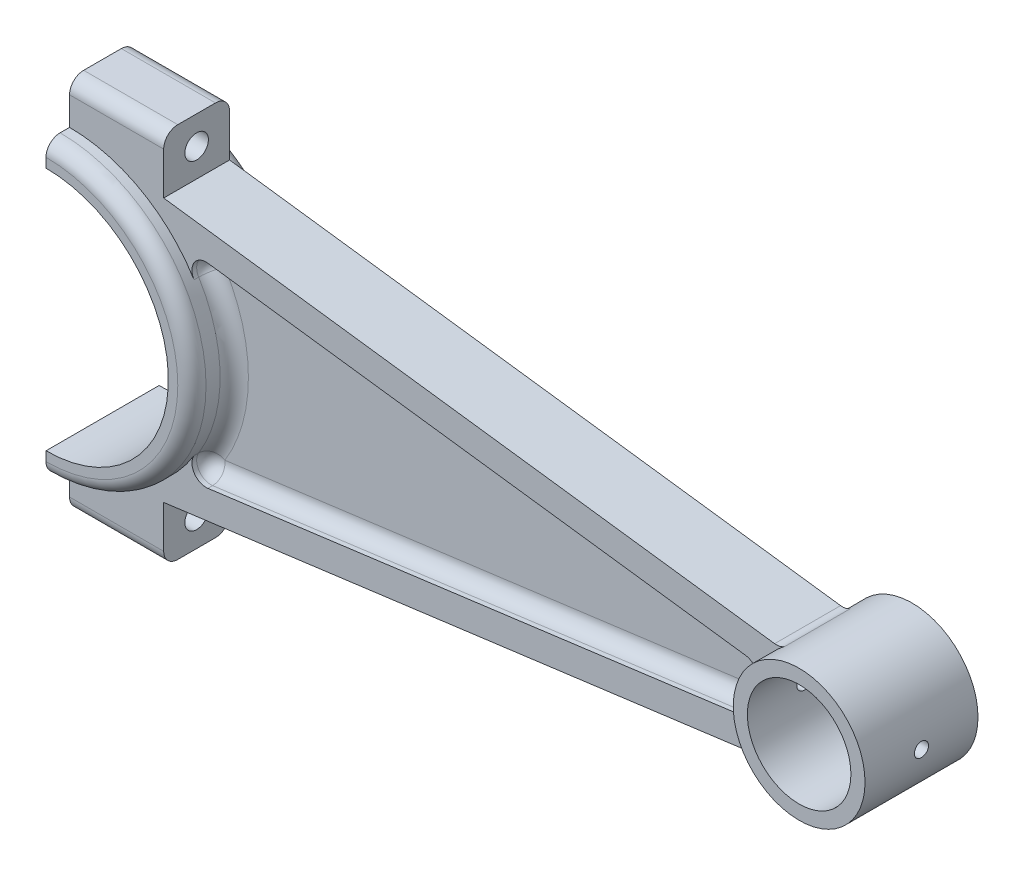
SolidWorks part; units mm, degrees
ref_plane "前视基准面" through (0, 0, 0) normal (0, 0, 1) x (1, 0, 0)
ref_plane "上视基准面" through (0, 0, 0) normal (0, 1, 0) x (1, 0, 0)
ref_plane "右视基准面" through (0, 0, 0) normal (1, 0, 0) x (0, 0, -1)
sketch "草图1" plane through (0, 0, 0) normal (0, 0, 1) x (1, 0, 0)
  line L0 (0, -40) -> (0, -26)
  line L1 (0, 40) -> (20, 40)
  line L2 (20, 40) -> (20, 28)
  line L3 (20, 28) -> (149.8009, 10.9114)
  line L4 (0, 0) -> (160, 0) construction
  line L5 (160, 55.8362) -> (160, -43.6894) construction
  line L6 (0, -40) -> (20, -40)
  line L7 (20, -28) -> (149.8009, -10.9114)
  line L8 (20, -40) -> (20, -28)
  line L9 (0, 26) -> (0, 40)
  arc A0 (0, -26) -> (0, 26) centre (0, 0) ccw
  arc A1 (151.9232, -11.4353) -> (151.9232, 11.4353) centre (160, 0) ccw
  arc A3 (149.8009, 10.9114) -> (151.9232, 11.4353) centre (150.1925, 13.8857) ccw
  arc A4 (149.8009, -10.9114) -> (151.9232, -11.4353) centre (150.1925, -13.8857) cw
  point P17 (20, 28)
  point P20 (151.0307, 10.7495)
  point P23 (151.0307, -10.7495)
  point P26 (20, -28)
  dimension "D1" = 160
  dimension "D2" = 20
  dimension "D3" = 12
  dimension "D4" = 97.5
extrude "拉伸1" add sketch "草图1" along normal blind 12
sketch "草图3" plane through (0, 0, 12) normal (0, 0, 1) x (1, 0, 0)
  arc A4 (151.9232, -11.4353) -> (151.9232, 11.4353) centre (160, 0) ccw construction
  arc A6 (151.9232, -11.4353) -> (151.9232, 11.4353) centre (160, 0) ccw
  circle A7 centre (160, 0) radius 11
extrude "切除-拉伸1" cut sketch "草图3" against normal through all contours A7
sketch "草图4" plane through (0, 0, 12) normal (0, 0, 1) x (1, 0, 0)
  line L0 (0, 40) -> (0, 26) construction
  line L1 (0, 40) -> (0, 31)
  line L2 (20, 28) -> (20, 40) construction
  line L3 (20, 40) -> (0, 40) construction
  line L4 (20, 28) -> (20, 40)
  line L5 (20, 40) -> (0, 40)
  line L6 (149.8009, 10.9114) -> (20, 28) construction
  line L7 (149.8009, 10.9114) -> (20, 28)
  line L8 (20, -40) -> (20, -28) construction
  line L9 (20, -28) -> (149.8009, -10.9114) construction
  line L10 (0, -40) -> (20, -40) construction
  line L11 (0, -26) -> (0, -40) construction
  line L12 (20, -40) -> (20, -28)
  line L13 (20, -28) -> (149.8009, -10.9114)
  line L14 (0, -40) -> (20, -40)
  line L15 (0, -31) -> (0, -40)
  arc A0 (0, -31) -> (0, 31) centre (0, 0) ccw
  arc A3 (151.9232, 11.4353) -> (151.9232, -11.4353) centre (160, 0) ccw
  arc A4 (149.8009, 10.9114) -> (151.9232, 11.4353) centre (150.1925, 13.8857) ccw construction
  arc A5 (149.8009, 10.9114) -> (151.9232, 11.4353) centre (150.1925, 13.8857) ccw
  arc A6 (151.9232, -11.4353) -> (149.8009, -10.9114) centre (150.1925, -13.8857) ccw construction
  arc A7 (151.9232, -11.4353) -> (149.8009, -10.9114) centre (150.1925, -13.8857) ccw
extrude "切除-拉伸2" cut sketch "草图4" against normal blind 5
sketch "草图5" plane through (0, 0, 7) normal (0, 0, 1) x (1, 0, 0)
  line L2 (149.0178, 4.9627) -> (19.2168, 22.0513)
  line L3 (143.6075, 5.675) -> (29.3987, 20.7109)
  line L5 (19.2168, -22.0513) -> (149.0178, -4.9627)
  line L6 (29.3987, -20.7109) -> (143.6075, -5.675)
  arc A0 (0, -31) -> (0, 31) centre (0, 0) ccw construction
  arc A1 (26.4477, -16.1715) -> (26.4477, 16.1715) centre (0, 0) ccw
  circle A2 centre (160, 0) radius 14 construction
  arc A3 (146.1778, 2.2241) -> (146.1778, -2.2241) centre (160, 0) ccw
  arc A4 (26.4477, 16.1715) -> (29.3987, 20.7109) centre (29.0072, 17.7365) cw
  arc A5 (26.4477, -16.1715) -> (29.3987, -20.7109) centre (29.0072, -17.7365) ccw
  arc A6 (143.6075, -5.675) -> (146.1778, -2.2241) centre (143.2159, -2.7007) ccw
  arc A7 (143.6075, 5.675) -> (146.1778, 2.2241) centre (143.2159, 2.7007) cw
  dimension "D3" = 3
  dimension "D1" = 6
  dimension "D2" = 6
extrude "切除-拉伸3" cut sketch "草图5" against normal blind 4
mirror "镜向1" about plane through (0, 0, 0) normal (0, 0, 1) of bodies 104
sketch "草图6" plane through (20, 0, 0) normal (1, 0, 0) x (0, 0, -1)
  circle A0 centre (0, -34) radius 2.5
extrude "切除-拉伸4" cut sketch "草图6" against normal through all
mirror "镜向2" about plane through (0, 0, 0) normal (0, 1, 0) of "切除-拉伸4"
fillet "圆角1" radius 3 11 edges at (26.492, 19.3717, 3) (86.5031, 13.1929, 3) (145.6219, 4.4927, 3) (146, 0, 3) (145.6219, -4.4927, 3) (86.5031, -13.1929, 3) (26.492, -19.3717, 3) (31, 0, 3) (31, 0, 12) (10, 40, 7) (10, -40, 7)
fillet "圆角2" radius 3 11 edges at (145.6219, 4.4927, -3) (146, 0, -3) (145.6219, -4.4927, -3) (86.5031, -13.1929, -3) (26.492, -19.3717, -3) (31, 0, -3) (26.492, 19.3717, -3) (10, 40, -7) (10, -40, -7) (31, 0, -12) (86.5031, 13.1929, -3)
sketch "草图7" plane through (0, 0, 0) normal (1, 0, 0) x (0, 0, -1)
  circle A0 centre (0, 0) radius 1.5
extrude "切除-拉伸6" cut sketch "草图7" along normal through all
